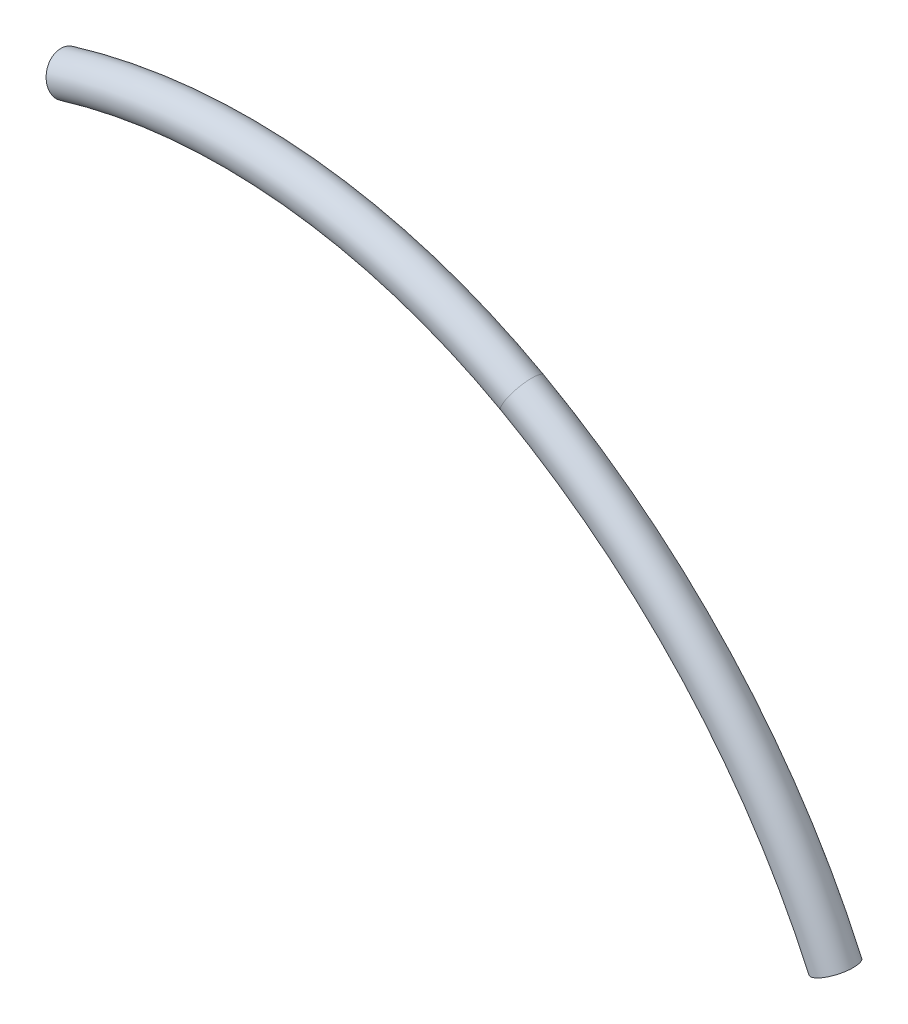
SolidWorks part; units mm, degrees
ref_plane "Front" through (0, 0, 0) normal (0, 0, 1) x (1, 0, 0)
ref_plane "Top" through (0, 0, 0) normal (0, 1, 0) x (1, 0, 0)
ref_plane "Right" through (0, 0, 0) normal (1, 0, 0) x (0, 0, -1)
sketch "Sketch1" plane through (0, 0, 0) normal (0, 0, 1) x (1, 0, 0)
  arc A0 (4111.7464, -1077.9471) -> (3300.9211, -195.5094) centre (2378.7278, -1856.595) ccw
  arc A1 (3300.9211, -195.5094) -> (2120.7701, -70.1343) centre (2562.9751, -1524.7227) ccw
  arc A2 (4336.743, -1804.0024) -> (4111.7464, -1077.9471) centre (1257.7011, -2360.274) ccw construction
  spline S0 degree 3 poles (12.6287, -1542.4185) (1660.0512, -1247.4612) (1396.184, -2572.0697) (2552.1536, -3378.376) (3653.2248, -3381.0744) (4498.8593, -2410.0471) (4234.3259, -1332.1122) (3828.4317, -438.5455) (2878.5173, 34.0308) (1828.4268, -38.3903) (848.7491, -832.9542) (478.3486, -2168.9227) (655.66, -3702.3879) (1776.0331, -4731.1943) (3233.2155, -4916.8204) (4680.4296, -4726.8399) (6307.3282, -3696.4175) (7469.1656, -2286.7006) (7106.2538, 15.9001) (6390.1027, 1605.915) (4943.9608, 2829.7833) (3528.655, 3564.3804) (2398.2908, 3971.4721) (81.6978, 4346.5877) (-2107.3471, 3741.776) (-3307.6994, 3064.2218) (-4872.4252, 2142.1063) (-6051.5753, 670.5262) (-6903.7379, -1042.8518) (-6660.4419, -2913.7021) (-4530.0051, -4010.9344) (-3278.8488, -4392.9339) (-2255.8989, -4955.8268) knots -0.03564 -0.03564 -0.03564 -0.03564 0.012418 0.026176 0.053223 0.077498 0.099256 0.122387 0.140197 0.165808 0.187601 0.21914 0.254189 0.284814 0.311917 0.350124 0.381709 0.440659 0.47622 0.524804 0.564919 0.59506 0.63529 0.679111 0.741875 0.781701 0.810098 0.866605 0.901783 0.935896 0.978749 1.043408 1.043408 1.043408 1.043408 only from (1640.1048, -2343.3491) to (-4072.3026, -4122.4591) construction
  dimension "D1" = 1219.2
  dimension "D2" = 1219.2
sketch "Sketch2" plane through (1093.6018, -2434.0041, 0) normal (-0.4098, 0.9122, 0) x (-0.9122, -0.4098, 0)
  circle A0 centre (-3308.7894, 0) radius 50.8
sweep "Sweep1" add profiles "Sketch2" path "Sketch1"
